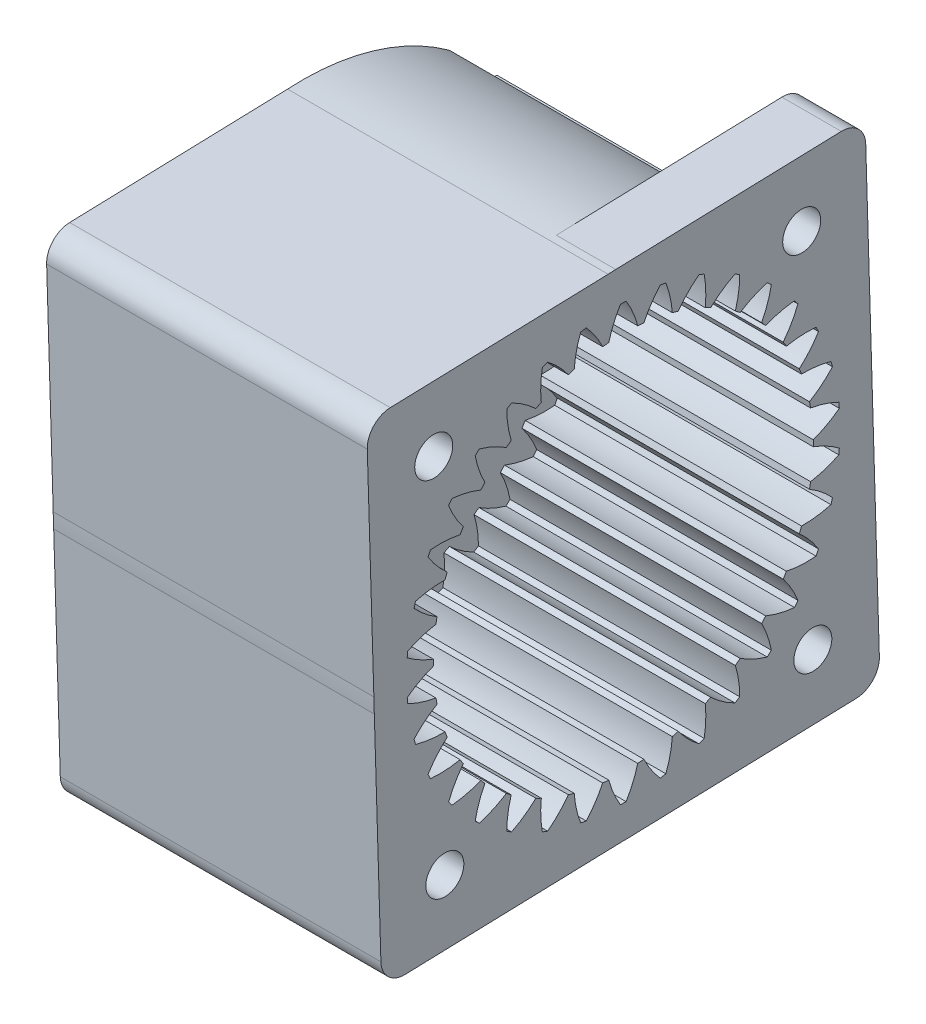
SolidWorks part; units mm, degrees
ref_plane "Plane1" through (0, 0, 0) normal (0, 0, 1) x (1, 0, 0)
ref_plane "Plane2" through (0, 0, 0) normal (0, 1, 0) x (1, 0, 0)
ref_plane "Plane3" through (0, 0, 0) normal (1, 0, 0) x (0, 0, -1)
sketch "HoldingSke" plane through (0, 0, 0) normal (0, 1, 0) x (1, 0, 0)
  line L0 (0, 0) -> (0.829, -0.5592)
  line L1 (-15, 0) -> (100, 0) construction
  line L2 (0, 0) -> (-2.1039, 2.3779)
  line L3 (0, 0) -> (-11.863, 4.5341)
  line L4 (0, 0) -> (7.1596, 4.8292)
  line L5 (0, 0) -> (-23.7986, -8.8762)
  line L6 (0, 0) -> (-10.5278, -7.1032)
  line L7 (-2.1039, 2.3779) -> (3.3635, 27.1825)
  line L8 (-76.2, 3.3779) -> (-54.61, 3.3779)
  line L9 (-71.009, 38.7566) -> (-53.1078, 45.2721)
  line L10 (-76.2, 71.12) -> (104.1128, 71.12)
  line L11 (0, 0) -> (-30, 0)
  line L12 (-76.2, 101.6) -> (-76.162, 101.6)
  line L13 (24.9733, 27.94) -> (52.9518, 28.4284)
  line L14 (24.9733, 27.94) -> (24.9743, 27.94)
  line L15 (24.9733, 27.94) -> (100.4006, 29.5858)
  circle A0 centre (0, 0) radius 21
  circle A1 centre (0, 0) radius 12.7
  circle A2 centre (0, 0) radius 12.7
  dimension "MHD" = 25.4
  dimension "Hub_dia" = 25.4
  dimension "Diameter" = 42
  dimension "Num_teeth" = 34
  dimension "Pitch" = 1
  dimension "Overall_len" = 25.4
  dimension "Show_teeth" = 34
  dimension "Thickness" = 12.7
  dimension "OAL" = 25.4001
  dimension "T_dim" = 21.59
  dimension "Ap" = 20
  dimension "H" = 19.05
  dimension "Pitch_radius" = 180.3128
  dimension "Width" = 30
  dimension "Backlash" = 0.038
  dimension "Addendum_fac" = 1
  dimension "Dedendum_fac" = 1.25
  dimension "Clearance_fac" = 0.25
  dimension "Dedendum_add" = 0.001
  dimension "Module" = 1
sketch "BasProSke" plane through (0, 0, 0) normal (0, 1, 0) x (1, 0, 0)
  line L0 (-10, 0) -> (60, 0) construction
  line L1 (0, 16) -> (0, 21)
  line L2 (0, 16) -> (30, 16)
  line L3 (30, 16) -> (30, 21)
  line L4 (30, 21) -> (0, 21)
  dimension "Diameter" = 42
  dimension "Thickness" = 30
  dimension "Inside_diameter" = 32
revolve "Base-Revolve" add sketch "BasProSke" angle 360 about L0
sketch "TooCutSke" plane through (0, 0, 0) normal (1, 0, 0) x (0, 0, -1)
  line L3 (0.8801, 16.9772) -> (0.8801, 53.6633) construction
  line L4 (0, 0) -> (0, 59.563) construction
  line L5 (0, 0) -> (-6.3045, 68.036) construction
  line L6 (-6.9998, 13.7903) -> (36.3548, 17.8077) construction
  circle A0 centre (0, 0) radius 17 construction
  circle A1 centre (0, 0) radius 18.251 construction
  circle A2 centre (0, 0) radius 14.3773 construction
  circle A3 centre (0, 0) radius 15.9746 construction
  arc A4 (1.2271, 15.9274) -> (0.2366, 18.2495) centre (-6.9998, 13.7903) ccw
  arc A5 (1.2271, 15.9274) -> (-1.2271, 15.9274) centre (0, 0) ccw
  arc A6 (0.2366, 18.2495) -> (-0.2366, 18.2495) centre (0, 0) ccw
  arc A7 (-0.2366, 18.2495) -> (-1.2271, 15.9274) centre (6.9998, 13.7903) ccw
  dimension "Pitch_dia" = 34
  dimension "Base_dia" = 28.7546
  dimension "Root_dia" = 36.502
  dimension "Overcut_dia" = 31.9492
  dimension "Flank_rad" = 8.5
  dimension "Half_ang" = 5.294
  dimension "Half_CT" = 0.8801
extrude "ToothCut" cut sketch "TooCutSke" along normal through all
fillet "Breaks" [suppressed] radius 0.1
fillet "RootFillets" [suppressed] radius 0.251
pattern_circular "TeethCuts" count 34 every 10.588 about axis through (-10, 0, 0) along (1, 0, 0) of "RootFillets", "Breaks", "ToothCut"
sketch "Sketch1" plane through (30, 0, 0) normal (1, 0, 0) x (0, 0, -1)
  line L1 (-21, 0) -> (-20.3468, -21.6149)
  line L2 (0, -21) -> (-20.3468, -21.6149)
  line L4 (-21, 0) -> (-21.6149, 20.3468)
  line L6 (0, 21) -> (-21.6149, 20.3468)
  circle A0 centre (0, 0) radius 21 construction
  arc A1 (0, 21) -> (0, -21) centre (0, 0) ccw
extrude "Boss-Extrude1" add sketch "Sketch1" against normal blind 30 contours A1 L6 L4 | A1 L1 L2
sketch "Sketch5" plane through (0, 0, 0) normal (-1, 0, 0) x (0, 0, 1)
  circle A0 centre (0, 0) radius 9
  circle A1 centre (0, 0) radius 19.3944
extrude "Boss-Extrude2" add sketch "Sketch5" against normal blind 5
sketch "Sketch6" plane through (30, 0, 0) normal (1, 0, 0) x (0, 0, -1)
  line L4 (-1.2681, 20.9617) -> (-21.6149, 20.3468)
  line L5 (-21.6149, 20.3468) -> (-21, 0)
  line L6 (-20.9617, -1.2681) -> (-20.3468, -21.6149)
  line L7 (-20.3468, -21.6149) -> (0, -21)
  line L8 (-1.2681, 20.9617) -> (-21.6149, 20.3468)
  line L9 (-21.6149, 20.3468) -> (-21, 0)
  line L10 (-20.9617, -1.2681) -> (-20.3468, -21.6149)
  line L11 (-20.3468, -21.6149) -> (0, -21)
  arc A2 (0, -21) -> (-1.2681, 20.9617) centre (0, 0) ccw
  arc A3 (-21, 0) -> (-20.9617, -1.2681) centre (0, 0) ccw
  arc A4 (0, -21) -> (-1.2681, 20.9617) centre (0, 0) ccw
  arc A5 (-21, 0) -> (-20.9617, -1.2681) centre (0, 0) ccw
  dimension "D1" = 0
extrude "Cut-Extrude3" cut sketch "Sketch6" against normal blind 3
sketch "Sketch7" plane through (27, 0, 0) normal (1, 0, 0) x (0, 0, -1)
  line L0 (21.6247, -20.3561) -> (0.6343, -20.9904)
  line L1 (21.6247, -20.3561) -> (20.3561, 21.6247)
  line L3 (20.3561, 21.6247) -> (-0.6343, 20.9904)
  arc A5 (0, -21) -> (-1.2681, 20.9617) centre (0, 0) ccw construction
  arc A6 (0.6343, -20.9904) -> (-0.6343, 20.9904) centre (0, 0) ccw
  point P4 (0, 0)
  point P12 (0, 0)
extrude "Boss-Extrude3" add sketch "Sketch7" against normal blind 5 contours A6 L1 L3 | A6 L0 L1
sketch "Sketch3" plane through (0, 0, 0) normal (-1, 0, 0) x (0, 0, 1)
  circle A0 centre (15.9611, 15.0247) radius 1.6
  circle A2 centre (15.0247, -15.9611) radius 1.6
  circle A3 centre (-15.9611, -15.0247) radius 1.6
  circle A4 centre (-15.0247, 15.9611) radius 1.6
  point P13 (0, 0)
  dimension "D1" = 4
extrude "Cut-Extrude1" cut sketch "Sketch3" against normal through all
sketch "Sketch9" plane through (0, 0, 0) normal (-1, 0, 0) x (0, 0, 1)
  line L1 (-11.7916, 15.9611) -> (-13.4082, 18.7611)
  line L2 (-13.4082, 18.7611) -> (-16.6413, 18.7611)
  line L3 (-16.6413, 18.7611) -> (-18.2579, 15.9611)
  line L4 (-18.2579, 15.9611) -> (-16.6413, 13.1611)
  line L5 (-16.6413, 13.1611) -> (-13.4082, 13.1611)
  line L6 (-13.4082, 13.1611) -> (-11.7916, 15.9611)
  line L7 (-12.728, -15.0247) -> (-14.3445, -12.2247)
  line L8 (-14.3445, -12.2247) -> (-17.5777, -12.2247)
  line L9 (-17.5777, -12.2247) -> (-19.1943, -15.0247)
  line L10 (-19.1943, -15.0247) -> (-17.5777, -17.8247)
  line L11 (-17.5777, -17.8247) -> (-14.3445, -17.8247)
  line L12 (-14.3445, -17.8247) -> (-12.728, -15.0247)
extrude "Cut-Extrude4" cut sketch "Sketch9" against normal up to surface (22 mm away) up to face at (22, 15.4894, -14.5807)
fillet "Fillet1" radius 2 4 edges at (13.5, 20.3468, 21.6149) (13.5, -21.6149, 20.3468) (24.5, -20.3561, -21.6247) (24.5, 21.6247, -20.3561)
equation "' \"Module@HoldingSke\" = 6.35"
equation "' \"Num_teeth@HoldingSke\" = 24"
equation "' \"Ap@HoldingSke\" =  14.5"
equation "' \"Ap@HoldingSke\" = 14.5"
equation "' \"Width@HoldingSke\" = 12"
equation "' \"Diameter@HoldingSke\" = 8 * 25.4"
equation "' \"Show_teeth@HoldingSke\" = 100"
equation "' \"Backlash@HoldingSke\" = 0.009 * 25.4"
equation "' \"Addendum_fac@HoldingSke\" = 1.0"
equation "' \"Dedendum_fac@HoldingSke\" = 1.25"
equation "' \"Dedendum_add@HoldingSke\" = 0.00005 * 25.4"
equation "' \"Clearance_fac@HoldingSke\" = 0.25"
equation "\"Pitch@HoldingSke\" = 1 / \"Module@HoldingSke\" "
equation "\"Overcut_dia@TooCutSke\" = (\"Num_teeth@HoldingSke\" - 2 * \"Addendum_fac@HoldingSke\") / \"Pitch@HoldingSke\" - 0.002 * 25.4"
equation "\"Pitch_dia@TooCutSke\" = \"Num_teeth@HoldingSke\" / \"Pitch@HoldingSke\""
equation "\"Base_dia@TooCutSke\" = \"Num_teeth@HoldingSke\" / \"Pitch@HoldingSke\" * cos((\"Ap@HoldingSke\"  * 3.14159265 / 180)) * 0.90"
equation "\"Root_dia@TooCutSke\" = \"Num_teeth@HoldingSke\"  / \"Pitch@HoldingSke\" + 2 *  \"Dedendum_fac@HoldingSke\"/ \"Pitch@HoldingSke\" + \"Dedendum_add@HoldingSke\" * 2"
equation "\"Half_ang@TooCutSke\" = 180 / \"Num_teeth@HoldingSke\""
equation "\"Half_CT@TooCutSke\" = \"Num_teeth@HoldingSke\" / \"Pitch@HoldingSke\" * sin((3.14159265 / 2 / \"Num_teeth@HoldingSke\")) / 2 + 10 * \"Backlash@HoldingSke\" / 4"
equation "\"Flank_rad@TooCutSke\" = \"Num_teeth@HoldingSke\" / \"Pitch@HoldingSke\" / 4"
equation "\"Radius@RootFillets\"= \"Clearance_fac@HoldingSke\" / \"Pitch@HoldingSke\" + \"Dedendum_add@HoldingSke\""
equation "\"Break_rad@Breaks\" = 0.02 / \"Pitch@HoldingSke\" * 5"
equation "\"Num_teeth@TeethCuts\" = int( \"Show_teeth@HoldingSke\" ) + 1"
equation "\"Num_teeth@TeethCuts\" = ((sgn( \"Num_teeth@TeethCuts\" - \"Num_teeth@HoldingSke\" )-1)*( \"Num_teeth@TeethCuts\" - \"Num_teeth@HoldingSke\" ))/-2+ \"Num_teeth@HoldingSke\""
equation "\"Num_teeth@TeethCuts\" = ((sgn( \"Num_teeth@TeethCuts\" - 2.0)+1)*( \"Num_teeth@TeethCuts\" - 2.0))/2 +2.0"
equation "\"Angle@TeethCuts\" = 360.0 / \"Num_teeth@HoldingSke\""
equation "\"Diameter@BasProSke\" = \"Num_teeth@HoldingSke\"  / \"Pitch@HoldingSke\" + 2 *  \"Dedendum_fac@HoldingSke\"/ \"Pitch@HoldingSke\" + \"Dedendum_add@HoldingSke\" * 2 + 0.002 * 25.4"
equation "\"Diameter@BasProSke\" = ((sgn( \"Diameter@BasProSke\"  - \"Diameter@HoldingSke\" )+1)*( \"Diameter@BasProSke\"  - \"Diameter@HoldingSke\" ))/2 + \"Diameter@HoldingSke\""
equation "\"Inside_diameter@BasProSke\" =  (\"Num_teeth@HoldingSke\" - 2 * \"Addendum_fac@HoldingSke\") / \"Pitch@HoldingSke\" "
equation "\"Thickness@BasProSke\"  = \"Width@HoldingSke\""
